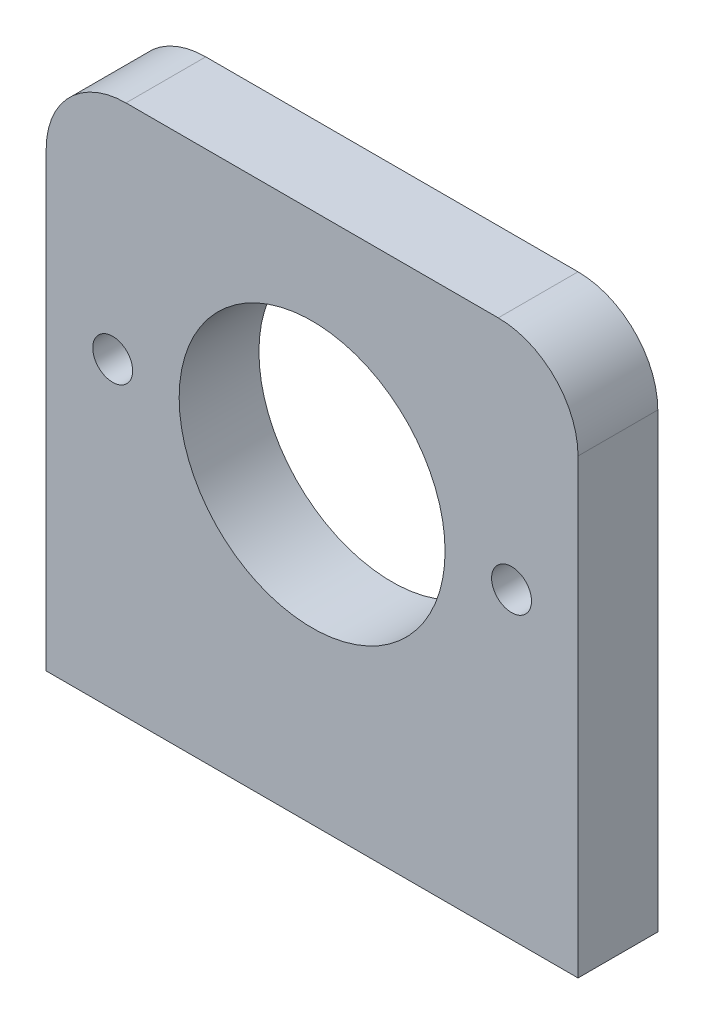
SolidWorks part; units mm, degrees
ref_plane "Front Plane" through (0, 0, 0) normal (0, 0, 1) x (1, 0, 0)
ref_plane "Top Plane" through (0, 0, 0) normal (0, 1, 0) x (1, 0, 0)
ref_plane "Right Plane" through (0, 0, 0) normal (1, 0, 0) x (0, 0, -1)
sketch "Sketch1" plane through (0, 0, 0) normal (0, 0, 1) x (1, 0, 0)
  line L1 (-50, -57) -> (50, -57)
  line L2 (-50, -57) -> (-50, 28)
  line L3 (-35, 43) -> (35, 43)
  line L4 (50, -57) -> (50, 28)
  line L6 (-50, 43) -> (-45.8904, 38.315) construction
  line L8 (46.1331, 38.0525) -> (50, 43) construction
  circle A0 centre (0, 0) radius 25
  arc A1 (35, 43) -> (50, 28) centre (35, 28) cw
  arc A2 (-50, 28) -> (-35, 43) centre (-35, 28) cw
  circle A3 centre (-37.5, 0) radius 3.75
  circle A4 centre (37.5, 0) radius 3.75
  point P0 (0, 0)
  point P19 (0, 0)
  point P20 (0, 0)
  point P25 (0, 0)
  point P26 (0, -57)
  point P27 (0, 0)
  dimension "D1" = 50
  dimension "D4" = 15
  dimension "D6" = 7.5
  dimension "D2" = 57
  dimension "D9" = 7.5
  dimension "D3" = 100
  dimension "D5" = 37.5
  dimension "D7" = 100
  dimension "D8" = 37.5
extrude "Boss-Extrude1" add sketch "Sketch1" along normal blind 15
